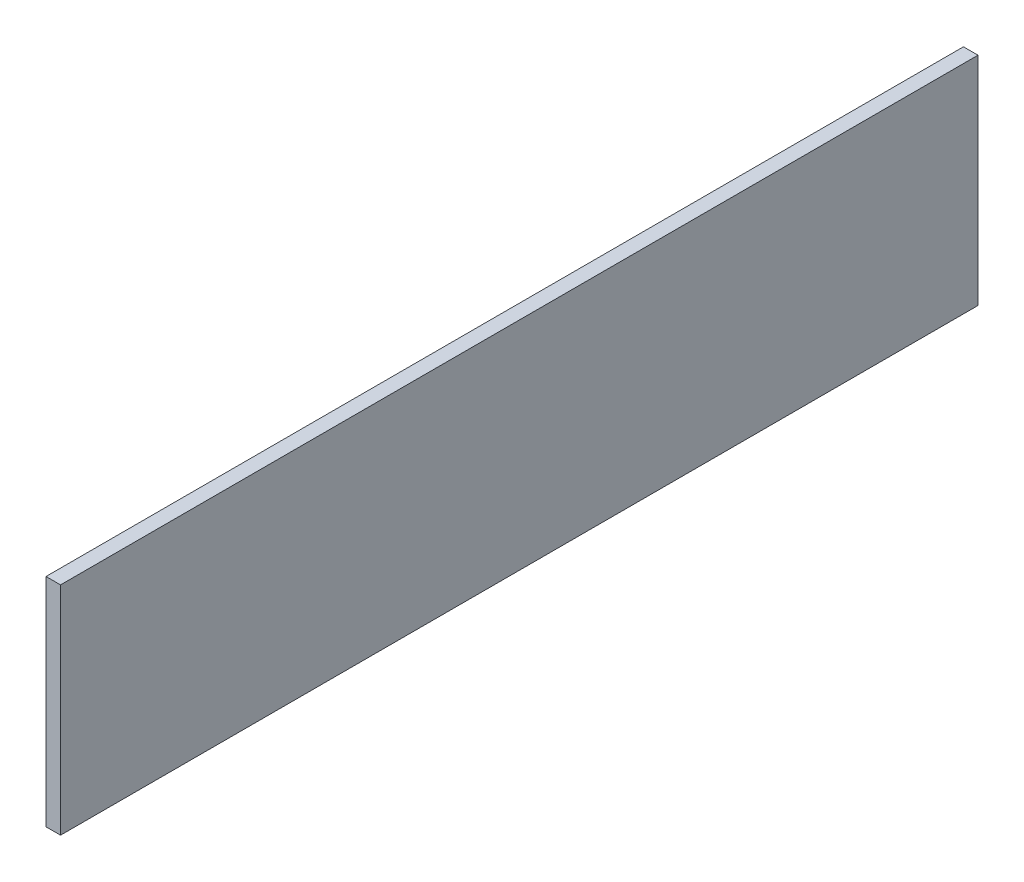
SolidWorks part; units mm, degrees
ref_plane "Front Plane" through (0, 0, 0) normal (0, 0, 1) x (1, 0, 0)
ref_plane "Top Plane" through (0, 0, 0) normal (0, 1, 0) x (1, 0, 0)
ref_plane "Right Plane" through (0, 0, 0) normal (1, 0, 0) x (0, 0, -1)
other "Configuration Table"
sketch "Sketch1" plane through (0, 0, 0) normal (0, 0, 1) x (1, 0, 0)
  line L1 (702, 1469) -> (714, 1469)
  line L2 (702, 1469) -> (702, 1648)
  line L3 (702, 1648) -> (714, 1648)
  line L4 (714, 1469) -> (714, 1648)
extrude "DET_bolme_saci_sol_1" add sketch "Sketch1" against normal blind 757.5 separate body
